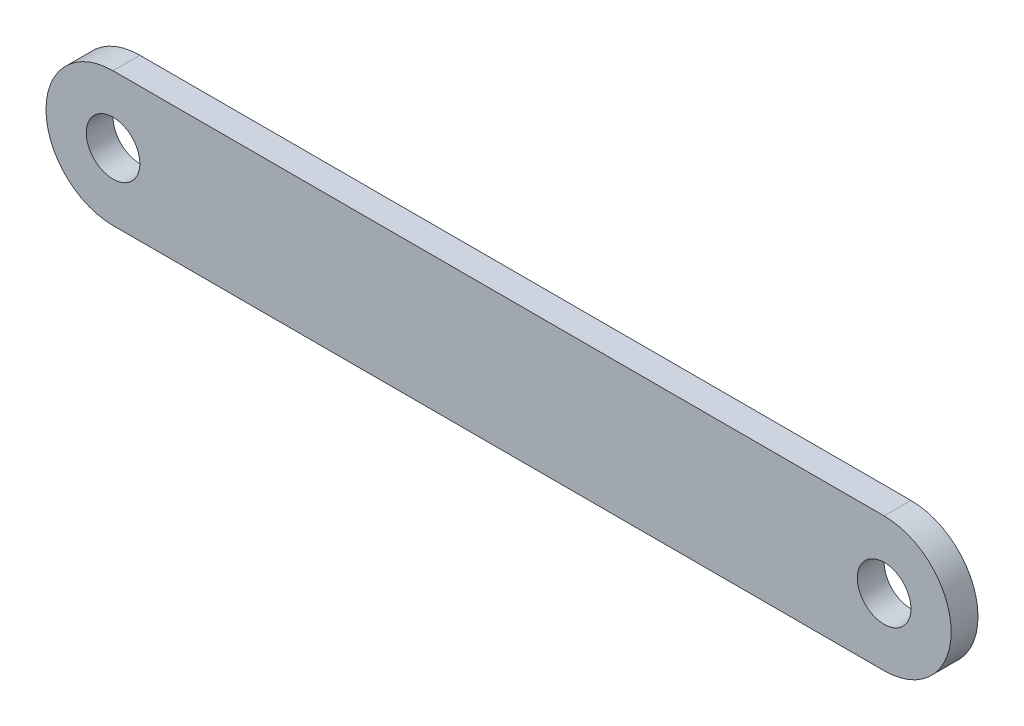
SolidWorks part; units mm, degrees
ref_plane "Front Plane" through (0, 0, 0) normal (0, 0, 1) x (1, 0, 0)
ref_plane "Top Plane" through (0, 0, 0) normal (0, 1, 0) x (1, 0, 0)
ref_plane "Right Plane" through (0, 0, 0) normal (1, 0, 0) x (0, 0, -1)
sketch "Sketch1" plane through (0, 0, 0) normal (0, 0, 1) x (1, 0, 0)
  line L0 (0, 5) -> (57.5, 5)
  line L2 (0, -5) -> (57.5, -5)
  arc A0 (0, 5) -> (0, -5) centre (0, 0) ccw
  arc A1 (57.5, -5) -> (57.5, 5) centre (57.5, 0) ccw
  circle A2 centre (0, 0) radius 2
  circle A3 centre (57.5, 0) radius 2
  dimension "D1" = 10
  dimension "D2" = 10
  dimension "D5" = 4
  dimension "D6" = 4
  dimension "D3" = 57.5
extrude "Boss-Extrude1" add sketch "Sketch1" along normal blind 2
